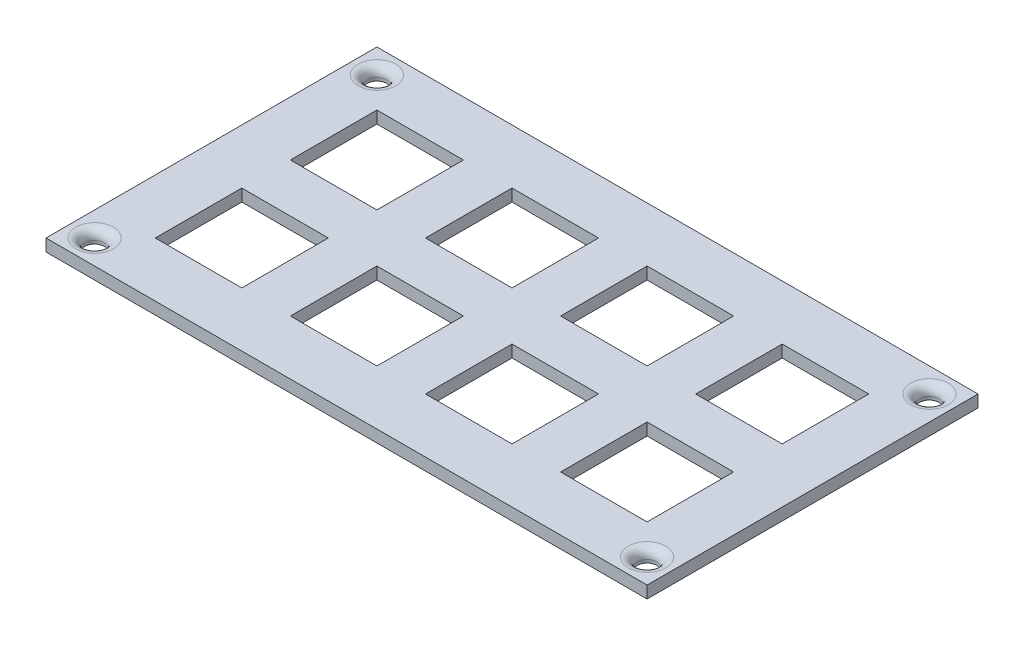
SolidWorks part; units mm, degrees
ref_plane "Front Plane" through (0, 0, 0) normal (0, 0, 1) x (1, 0, 0)
ref_plane "Top Plane" through (0, 0, 0) normal (0, 1, 0) x (1, 0, 0)
ref_plane "Right Plane" through (0, 0, 0) normal (1, 0, 0) x (0, 0, -1)
sketch "Sketch1" plane through (0, 0, 0) normal (0, 1, 0) x (1, 0, 0)
  line L0 (-49.5, 0) -> (49.5, 0) construction
  line L1 (-40.5, 18.25) -> (-26.25, 18.25)
  line L2 (-40.5, 18.25) -> (-40.5, 4)
  line L3 (-40.5, 4) -> (-26.25, 4)
  line L4 (-26.25, 18.25) -> (-26.25, 4)
  line L5 (-49.5, 27.25) -> (49.5, 27.25)
  line L6 (-49.5, 27.25) -> (-49.5, -27.25)
  line L7 (-49.5, -27.25) -> (49.5, -27.25)
  line L8 (49.5, 27.25) -> (49.5, -27.25)
  line L9 (0, 27.25) -> (0, -27.25) construction
  line L10 (-18.25, 18.25) -> (-18.25, 4)
  line L11 (-18.25, 18.25) -> (-4, 18.25)
  line L12 (-4, 18.25) -> (-4, 4)
  line L13 (-18.25, 4) -> (-4, 4)
  line L14 (18.25, 18.25) -> (4, 18.25)
  line L15 (4, 18.25) -> (4, 4)
  line L16 (18.25, 4) -> (4, 4)
  line L17 (18.25, 18.25) -> (18.25, 4)
  line L18 (40.5, 4) -> (26.25, 4)
  line L19 (26.25, 18.25) -> (26.25, 4)
  line L20 (40.5, 18.25) -> (26.25, 18.25)
  line L21 (40.5, 18.25) -> (40.5, 4)
  line L22 (40.5, -18.25) -> (40.5, -4)
  line L23 (40.5, -18.25) -> (26.25, -18.25)
  line L24 (26.25, -18.25) -> (26.25, -4)
  line L25 (40.5, -4) -> (26.25, -4)
  line L26 (18.25, -18.25) -> (18.25, -4)
  line L27 (18.25, -4) -> (4, -4)
  line L28 (4, -18.25) -> (4, -4)
  line L29 (18.25, -18.25) -> (4, -18.25)
  line L30 (-18.25, -18.25) -> (-4, -18.25)
  line L31 (-4, -18.25) -> (-4, -4)
  line L32 (-18.25, -4) -> (-4, -4)
  line L33 (-18.25, -18.25) -> (-18.25, -4)
  line L34 (-40.5, -4) -> (-26.25, -4)
  line L35 (-26.25, -18.25) -> (-26.25, -4)
  line L36 (-40.5, -18.25) -> (-26.25, -18.25)
  line L37 (-40.5, -18.25) -> (-40.5, -4)
  circle A0 centre (-45.5, 23.25) radius 1.6
  circle A1 centre (45.5, 23.25) radius 1.6
  circle A2 centre (45.5, -23.25) radius 1.6
  circle A3 centre (-45.5, -23.25) radius 1.6
  point P8 (0, 27.25)
  point P10 (-49.5, 0)
  dimension "D11" = 3.2
  dimension "D1" = 14.25
  dimension "D2" = 14.25
  dimension "D4" = 8
  dimension "D5" = 4
  dimension "D6" = 4
  dimension "D7" = 9
  dimension "D8" = 9
  dimension "D9" = 4
  dimension "D10" = 4
  dimension "D3" = 2
extrude "Boss-Extrude1" add sketch "Sketch1" along normal blind 2
fillet "Fillet1" radius 1.5 4 edges at (-45.5, 2, 21.65) (45.5, 2, 24.85) (45.5, 2, -24.85) (-45.5, 2, -21.65)
